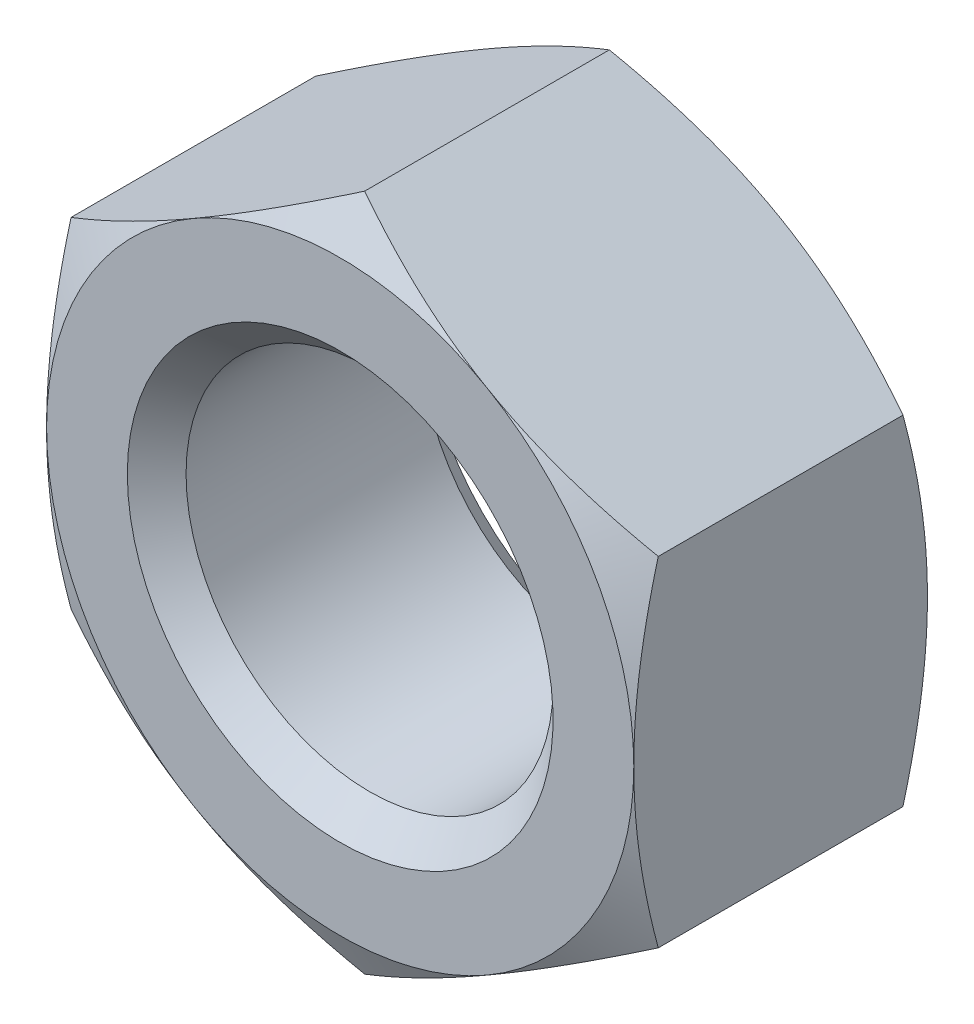
SolidWorks part; units mm, degrees
material "Plain Carbon Steel"
ref_plane "Front Plane" through (0, 0, 0) normal (0, 0, 1) x (1, 0, 0)
ref_plane "Top Plane" through (0, 0, 0) normal (0, 1, 0) x (1, 0, 0)
ref_plane "Right Plane" through (0, 0, 0) normal (1, 0, 0) x (0, 0, -1)
sketch "Sketch1" plane through (0, 0, 0) normal (0, 0, 1) x (1, 0, 0)
  line L1 (0, -4.6188) -> (4, -2.3094)
  line L2 (4, -2.3094) -> (4, 2.3094)
  line L3 (4, 2.3094) -> (0, 4.6188)
  line L4 (0, 4.6188) -> (-4, 2.3094)
  line L5 (-4, 2.3094) -> (-4, -2.3094)
  line L6 (-4, -2.3094) -> (0, -4.6188)
  circle A0 centre (0, 0) radius 4 construction
  circle A1 centre (0, 0) radius 2.5
  dimension "D2" = 5
  dimension "D1" = 8
extrude "Boss-Extrude1" add sketch "Sketch1" along normal blind 4
sketch "Sketch2" plane through (0, 0, 0) normal (1, 0, 0) x (0, 0, -1)
  line L0 (-4, 4.6188) -> (-4, 4)
  line L1 (-4, 2.3094) -> (-4, 4.6188) construction
  line L2 (-4, 4) -> (-3.6667, 4.6188)
  line L3 (-4, 4.6188) -> (0, 4.6188) construction
  line L4 (-3.6667, 4.6188) -> (-4, 4.6188)
  line L5 (-0.3333, 4.6188) -> (0, 4.6188)
  line L6 (0, 4.6188) -> (0, 4)
  line L7 (0, 2.3094) -> (0, 4.6188) construction
  line L8 (0, 4) -> (-0.3333, 4.6188)
  line L9 (-3.6667, 4.6188) -> (-3.3333, 4.6188) construction
  line L10 (-3.3333, 4.6188) -> (-3, 4.6188) construction
  line L11 (-3, 4.6188) -> (-2.6667, 4.6188) construction
  line L12 (-2.6667, 4.6188) -> (-2.3333, 4.6188) construction
  line L13 (-2.3333, 4.6188) -> (-2, 4.6188) construction
  line L14 (-2, 4.6188) -> (-1.6667, 4.6188) construction
  line L15 (-1.6667, 4.6188) -> (-1.3333, 4.6188) construction
  line L16 (-1.3333, 4.6188) -> (-1, 4.6188) construction
  line L17 (-1, 4.6188) -> (-0.6667, 4.6188) construction
  line L18 (0, 0) -> (-4, 0) construction
  line L19 (-4, -2.3094) -> (-4, 2.3094) construction
  line L20 (-4, 2.5) -> (-3.6, 2.5)
  line L21 (-3.6, 2.5) -> (-4, 2.9)
  line L22 (-4, 2.9) -> (-4, 2.5)
  line L23 (0, 2.5) -> (-0.4, 2.5)
  line L24 (0, -2.3094) -> (0, 2.3094) construction
  line L25 (-0.4, 2.5) -> (0, 2.9)
  line L26 (0, 2.9) -> (0, 2.5)
  line L29 (-3.6, 2.5) -> (-3.2, 2.5) construction
  line L30 (-3.2, 2.5) -> (-2.8, 2.5) construction
  line L31 (-2.8, 2.5) -> (-2.4, 2.5) construction
  line L32 (-2.4, 2.5) -> (-2, 2.5) construction
  line L33 (-2, 2.5) -> (-1.6, 2.5) construction
  line L34 (-1.6, 2.5) -> (-1.2, 2.5) construction
  line L35 (-1.2, 2.5) -> (-0.8, 2.5) construction
  line L36 (-0.8, 2.5) -> (-0.4, 2.5) construction
  line L37 (-0.6667, 4.6188) -> (-0.3333, 4.6188) construction
  dimension "D1" = 8
revolve "Cut-Revolve1" cut sketch "Sketch2" angle 360 about L18
